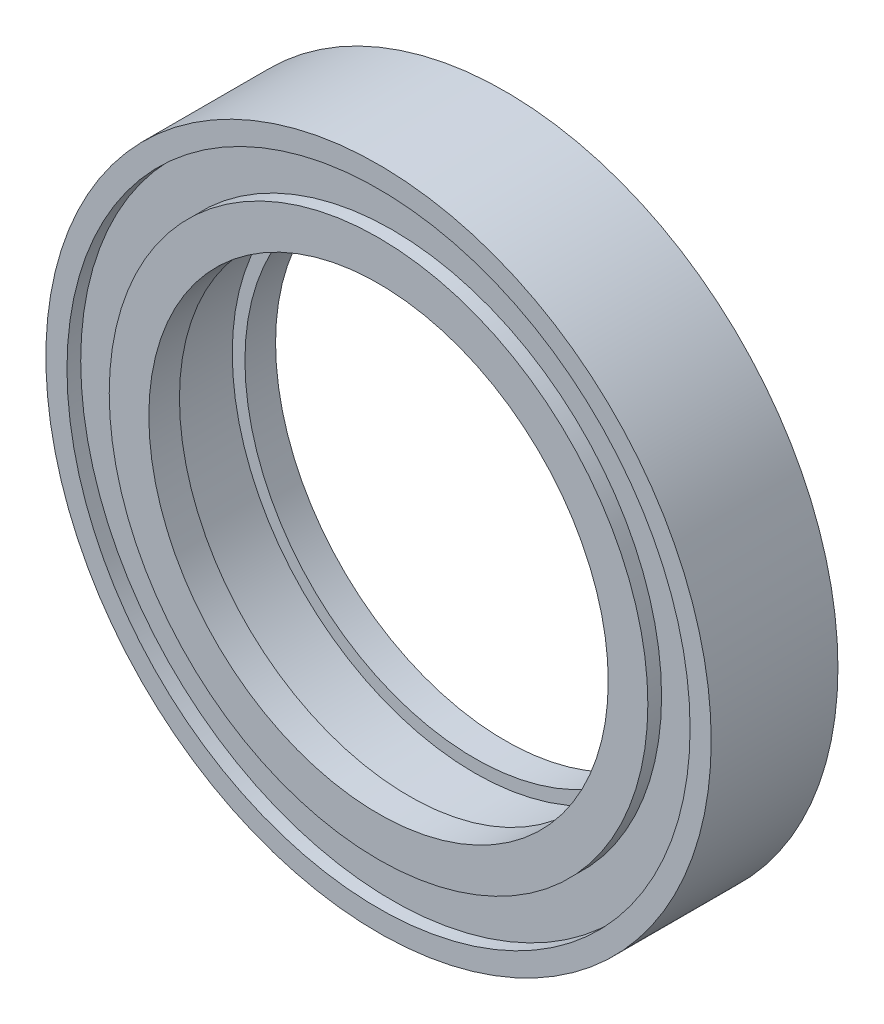
SolidWorks part; units mm, degrees
material "Custom Plastic"
ref_plane "Front Plane" through (0, 0, 0) normal (0, 0, 1) x (1, 0, 0)
ref_plane "Top Plane" through (0, 0, 0) normal (0, 1, 0) x (1, 0, 0)
ref_plane "Right Plane" through (0, 0, 0) normal (1, 0, 0) x (0, 0, -1)
sketch "Sketch1" plane through (0, 0, 0) normal (0, 1, 0) x (1, 0, 0)
  line L0 (0, -1000) -> (0, 49000) construction
  line L1 (-315, 60) -> (-295, 60)
  line L2 (-295, 60) -> (-295, 47)
  line L3 (-295, 47) -> (-255, 47)
  line L13 (-255, -47) -> (-295, -47)
  line L14 (-295, -47) -> (-295, -60)
  line L15 (-295, -60) -> (-315, -60)
  line L16 (-315, -60) -> (-315, 60)
  line L17 (-255, 47) -> (-255, 60)
  line L18 (-255, 60) -> (-217.5, 60)
  line L19 (-217.5, 60) -> (-217.5, 31)
  line L20 (-217.5, 31) -> (-229.5, 31)
  line L21 (-229.5, 31) -> (-229.5, -31)
  line L22 (-229.5, -31) -> (-217.5, -31)
  line L23 (-217.5, -31) -> (-217.5, -60)
  line L24 (-217.5, -60) -> (-255, -60)
  line L25 (-255, -60) -> (-255, -47)
  point P9 (-315, 0)
  point P14 (-275, -47)
  point P21 (-275, 47)
  dimension "D2" = 40
  dimension "D3" = 20
  dimension "D4" = 40
  dimension "D5" = 37.5
  dimension "D6" = 590
  dimension "D7" = 13
  dimension "D8" = 13
  dimension "D9" = 29
  dimension "D10" = 62
  dimension "D11" = 12
  dimension "D12" = 12
  dimension "D13" = 29
  dimension "D14" = 37.5
  dimension "D15" = 120
  dimension "D16" = 510
  dimension "D17" = 630
revolve "Revolve1" add sketch "Sketch1" angle 360 about L0
